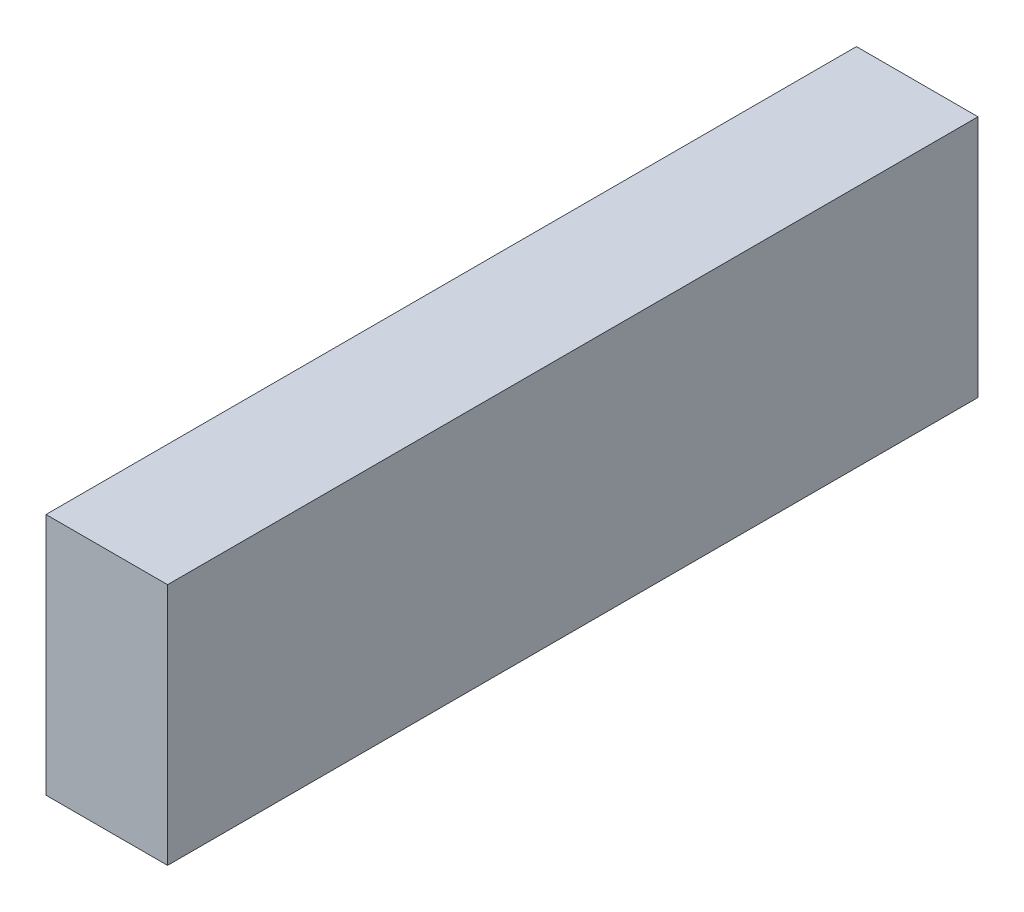
SolidWorks part; units mm, degrees
ref_plane "Front Plane" through (0, 0, 0) normal (0, 0, 1) x (1, 0, 0)
ref_plane "Top Plane" through (0, 0, 0) normal (0, 1, 0) x (1, 0, 0)
ref_plane "Right Plane" through (0, 0, 0) normal (1, 0, 0) x (0, 0, -1)
sketch "Sketch1" plane through (0, 0, 0) normal (0, 0, 1) x (1, 0, 0)
  line L1 (-1.5, 3) -> (1.5, 3)
  line L2 (-1.5, 3) -> (-1.5, -3)
  line L3 (-1.5, -3) -> (1.5, -3)
  line L4 (1.5, 3) -> (1.5, -3)
  line L5 (-1.5, 3) -> (1.5, -3) construction
  line L6 (-1.5, -3) -> (1.5, 3) construction
  point P0 (0, 0)
  dimension "D1" = 6
  dimension "D2" = 3
extrude "Boss-Extrude1" add sketch "Sketch1" along normal blind 20
